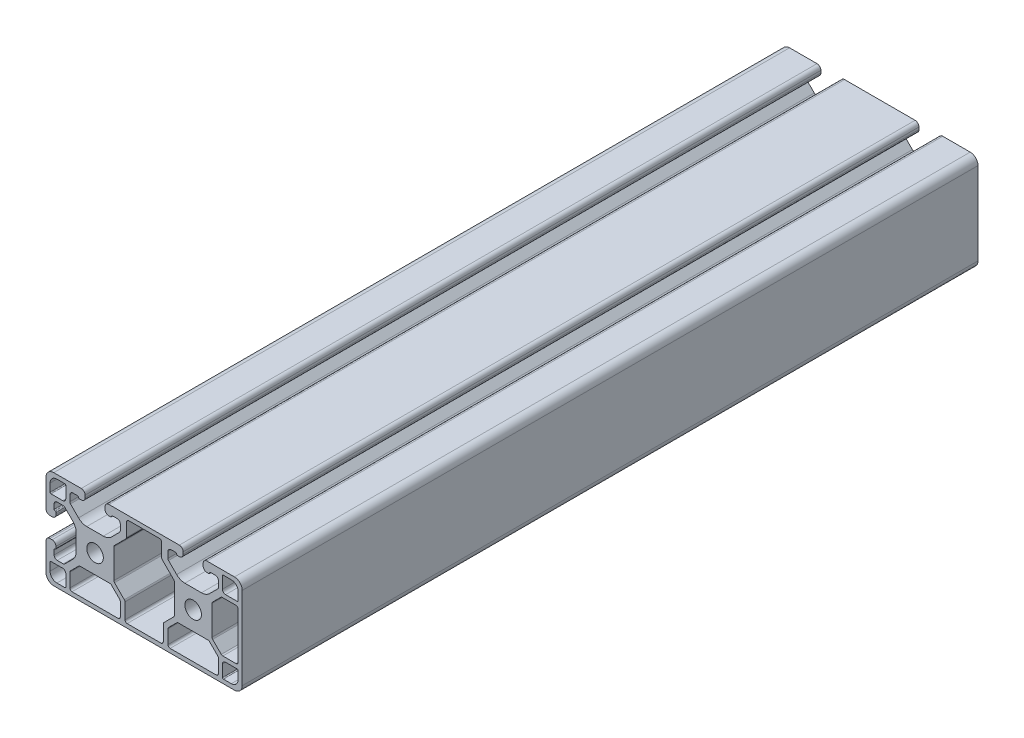
SolidWorks part; units mm, degrees
material "6105-T5 Aluminum"
ref_plane "Front Plane" through (0, 0, 0) normal (0, 0, 1) x (1, 0, 0)
ref_plane "Top Plane" through (0, 0, 0) normal (0, 1, 0) x (1, 0, 0)
ref_plane "Right Plane" through (0, 0, 0) normal (1, 0, 0) x (0, 0, -1)
sketch "Sketch1" plane through (0, 0, 0) normal (0, 0, 1) x (1, 0, 0)
  line L0 (-57.9695, -11.9365) -> (-53.2063, -11.9365)
  line L1 (-51.9365, -13.2063) -> (-51.9365, -17.9693)
  line L2 (-52.3165, -18.3492) -> (-55.5555, -18.3492)
  line L3 (-58.3495, -15.5552) -> (-58.3495, -12.3165)
  line L4 (-53.2063, 11.9365) -> (-57.9695, 11.9365)
  line L5 (-58.3495, 12.3165) -> (-58.3495, 15.5552)
  line L6 (-55.5555, 18.3492) -> (-52.3165, 18.3492)
  line L7 (-51.9365, 17.9693) -> (-51.9365, 13.2063)
  line L8 (13.2063, -11.9365) -> (17.9695, -11.9365)
  line L9 (18.3495, -12.3165) -> (18.3495, -15.5552)
  line L10 (15.5555, -18.3492) -> (12.3165, -18.3492)
  line L11 (11.9365, -17.9693) -> (11.9365, -13.2063)
  line L12 (17.9695, 11.9365) -> (13.2063, 11.9365)
  line L13 (11.9365, 13.2063) -> (11.9365, 17.9693)
  line L14 (12.3165, 18.3492) -> (15.5555, 18.3492)
  line L15 (18.3495, 15.5552) -> (18.3495, 12.3165)
  line L16 (-30.6032, -18.3492) -> (-49.3968, -18.3492)
  line L17 (-50.2857, -17.4603) -> (-50.2857, -11.911)
  line L18 (-50.0254, -11.2824) -> (-46.6858, -7.9429)
  line L19 (-46.0573, -7.6825) -> (-33.9427, -7.6825)
  line L20 (-33.3142, -7.9429) -> (-29.9746, -11.2824)
  line L21 (-29.7143, -11.911) -> (-29.7143, -17.4603)
  line L22 (-28.0699, -10.4935) -> (-32.0571, -6.5062)
  line L23 (-32.3175, -5.8777) -> (-32.3175, 6.0573)
  line L24 (-32.0571, 6.6858) -> (-27.435, 11.308)
  line L25 (-27.1746, 11.9365) -> (-27.1746, 17.4216)
  line L26 (-26.2857, 18.3105) -> (-13.7143, 18.3105)
  line L27 (-12.8254, 17.4216) -> (-12.8254, 11.9365)
  line L28 (-12.565, 11.308) -> (-7.9429, 6.6858)
  line L29 (-7.6825, 6.0573) -> (-7.6825, -5.8777)
  line L30 (-7.9429, -6.5062) -> (-11.9301, -10.4935)
  line L31 (-12.1905, -11.122) -> (-12.1905, -17.4603)
  line L32 (-13.0794, -18.3492) -> (-26.9206, -18.3492)
  line L33 (-27.8095, -17.4603) -> (-27.8095, -11.122)
  line L34 (6.6858, -7.9429) -> (10.0253, -11.2824)
  line L35 (10.2857, -11.911) -> (10.2857, -17.4603)
  line L36 (9.3968, -18.3492) -> (-9.3968, -18.3492)
  line L37 (-10.2857, -17.4603) -> (-10.2857, -11.911)
  line L38 (-10.0254, -11.2824) -> (-6.6858, -7.9429)
  line L39 (-6.0573, -7.6825) -> (6.0572, -7.6825)
  line L40 (11.462, -10.0253) -> (7.9429, -6.5063)
  line L41 (7.6825, -5.8776) -> (7.6825, 6.0573)
  line L42 (7.9429, 6.6858) -> (11.2824, 10.0254)
  line L43 (11.911, 10.2857) -> (17.4216, 10.2857)
  line L44 (18.3105, 9.3968) -> (18.3105, -9.3968)
  line L45 (17.4216, -10.2857) -> (12.0906, -10.2857)
  line L46 (16.8254, 20) -> (5.6381, 20)
  line L47 (4.0635, 18.4254) -> (4.0635, 17.5111)
  line L48 (5.6381, 15.9365) -> (6.3446, 15.9365)
  line L49 (6.7243, 16.3032) -> (6.7253, 16.3317)
  line L50 (7.105, 16.6984) -> (9.0159, 16.6984)
  line L51 (10.2857, 15.4286) -> (10.2857, 12.9885)
  line L52 (10.0254, 12.3599) -> (6.739, 9.0736)
  line L53 (3.3808, 7.6825) -> (-3.3808, 7.6825)
  line L54 (-6.739, 9.0736) -> (-10.0254, 12.3599)
  line L55 (-10.2857, 12.9885) -> (-10.2857, 15.4286)
  line L56 (-9.0159, 16.6984) -> (-7.105, 16.6984)
  line L57 (-6.7253, 16.3317) -> (-6.7243, 16.3032)
  line L58 (-6.3446, 15.9365) -> (-5.6381, 15.9365)
  line L59 (-4.0635, 17.5111) -> (-4.0635, 18.4254)
  line L60 (-5.6381, 20) -> (-34.3619, 20)
  line L61 (-35.9365, 18.4254) -> (-35.9365, 17.5111)
  line L62 (-34.3619, 15.9365) -> (-33.6554, 15.9365)
  line L63 (-33.2757, 16.3032) -> (-33.2747, 16.3317)
  line L64 (-32.895, 16.6984) -> (-30.9841, 16.6984)
  line L65 (-29.7143, 15.4286) -> (-29.7143, 12.9885)
  line L66 (-29.9746, 12.3599) -> (-33.261, 9.0736)
  line L67 (-36.6192, 7.6825) -> (-43.3808, 7.6825)
  line L68 (-46.739, 9.0736) -> (-50.0254, 12.3599)
  line L69 (-50.2857, 12.9885) -> (-50.2857, 15.4286)
  line L70 (-49.0159, 16.6984) -> (-47.105, 16.6984)
  line L71 (-46.7253, 16.3317) -> (-46.7243, 16.3032)
  line L72 (-46.3446, 15.9365) -> (-45.6381, 15.9365)
  line L73 (-44.0635, 17.5111) -> (-44.0635, 18.4254)
  line L74 (-45.6381, 20) -> (-56.8254, 20)
  line L75 (-60, 16.8254) -> (-60, 5.6381)
  line L76 (-58.4254, 4.0635) -> (-57.5111, 4.0635)
  line L77 (-55.9365, 5.6381) -> (-55.9365, 6.3446)
  line L78 (-56.3032, 6.7243) -> (-56.3317, 6.7253)
  line L79 (-56.6984, 7.105) -> (-56.6984, 9.0159)
  line L80 (-55.4286, 10.2857) -> (-52.9885, 10.2857)
  line L81 (-52.3599, 10.0254) -> (-49.0736, 6.739)
  line L82 (-47.6825, 3.3808) -> (-47.6825, -3.3808)
  line L83 (-49.0736, -6.739) -> (-52.3599, -10.0254)
  line L84 (-52.9885, -10.2857) -> (-55.4286, -10.2857)
  line L85 (-56.6984, -9.0159) -> (-56.6984, -7.105)
  line L86 (-56.3317, -6.7253) -> (-56.3032, -6.7243)
  line L87 (-55.9365, -6.3446) -> (-55.9365, -5.6381)
  line L88 (-57.5111, -4.0635) -> (-58.4254, -4.0635)
  line L89 (-60, -5.6381) -> (-60, -16.8254)
  line L90 (-56.8254, -20) -> (16.8254, -20)
  line L91 (20, -16.8254) -> (20, 16.8254)
  arc A0 (-51.9365, -13.2063) -> (-53.2063, -11.9365) centre (-53.2063, -13.2063) ccw
  arc A1 (-52.3165, -18.3492) -> (-51.9365, -17.9693) centre (-52.3165, -17.9693) ccw
  arc A2 (-58.3495, -15.5552) -> (-55.5555, -18.3492) centre (-55.5555, -15.5552) ccw
  arc A3 (-57.9695, -11.9365) -> (-58.3495, -12.3165) centre (-57.9695, -12.3165) ccw
  arc A4 (-58.3495, 12.3165) -> (-57.9695, 11.9365) centre (-57.9695, 12.3165) ccw
  arc A5 (-55.5555, 18.3492) -> (-58.3495, 15.5552) centre (-55.5555, 15.5552) ccw
  arc A6 (-51.9365, 17.9693) -> (-52.3165, 18.3492) centre (-52.3165, 17.9693) ccw
  arc A7 (-53.2063, 11.9365) -> (-51.9365, 13.2063) centre (-53.2063, 13.2063) ccw
  arc A8 (18.3495, -12.3165) -> (17.9695, -11.9365) centre (17.9695, -12.3165) ccw
  arc A9 (15.5555, -18.3492) -> (18.3495, -15.5552) centre (15.5555, -15.5552) ccw
  arc A10 (11.9365, -17.9693) -> (12.3165, -18.3492) centre (12.3165, -17.9693) ccw
  arc A11 (13.2063, -11.9365) -> (11.9365, -13.2063) centre (13.2063, -13.2063) ccw
  arc A12 (11.9365, 13.2063) -> (13.2063, 11.9365) centre (13.2063, 13.2063) ccw
  arc A13 (12.3165, 18.3492) -> (11.9365, 17.9693) centre (12.3165, 17.9693) ccw
  arc A14 (18.3495, 15.5552) -> (15.5555, 18.3492) centre (15.5555, 15.5552) ccw
  arc A15 (17.9695, 11.9365) -> (18.3495, 12.3165) centre (17.9695, 12.3165) ccw
  arc A16 (-30.6032, -18.3492) -> (-29.7143, -17.4603) centre (-30.6032, -17.4603) ccw
  arc A17 (-50.2857, -17.4603) -> (-49.3968, -18.3492) centre (-49.3968, -17.4603) ccw
  arc A18 (-50.0254, -11.2824) -> (-50.2857, -11.911) centre (-49.3968, -11.911) ccw
  arc A19 (-46.0573, -7.6825) -> (-46.6858, -7.9429) centre (-46.0573, -8.5714) ccw
  arc A20 (-33.3142, -7.9429) -> (-33.9427, -7.6825) centre (-33.9427, -8.5714) ccw
  arc A21 (-29.7143, -11.911) -> (-29.9746, -11.2824) centre (-30.6032, -11.911) ccw
  arc A22 (-27.8095, -11.122) -> (-28.0699, -10.4935) centre (-28.6984, -11.122) ccw
  arc A23 (-32.3175, -5.8777) -> (-32.0571, -6.5062) centre (-31.4286, -5.8777) ccw
  arc A24 (-32.0571, 6.6858) -> (-32.3175, 6.0573) centre (-31.4286, 6.0573) ccw
  arc A25 (-27.435, 11.308) -> (-27.1746, 11.9365) centre (-28.0635, 11.9365) ccw
  arc A26 (-26.2857, 18.3105) -> (-27.1746, 17.4216) centre (-26.2857, 17.4216) ccw
  arc A27 (-12.8254, 17.4216) -> (-13.7143, 18.3105) centre (-13.7143, 17.4216) ccw
  arc A28 (-12.8254, 11.9365) -> (-12.565, 11.308) centre (-11.9365, 11.9365) ccw
  arc A29 (-7.6825, 6.0573) -> (-7.9429, 6.6858) centre (-8.5714, 6.0573) ccw
  arc A30 (-7.9429, -6.5062) -> (-7.6825, -5.8777) centre (-8.5714, -5.8777) ccw
  arc A31 (-11.9301, -10.4935) -> (-12.1905, -11.122) centre (-11.3016, -11.122) ccw
  arc A32 (-13.0794, -18.3492) -> (-12.1905, -17.4603) centre (-13.0794, -17.4603) ccw
  arc A33 (-27.8095, -17.4603) -> (-26.9206, -18.3492) centre (-26.9206, -17.4603) ccw
  arc A34 (10.2857, -11.911) -> (10.0253, -11.2824) centre (9.3967, -11.911) ccw
  arc A35 (9.3968, -18.3492) -> (10.2857, -17.4603) centre (9.3968, -17.4603) ccw
  arc A36 (-10.2857, -17.4603) -> (-9.3968, -18.3492) centre (-9.3968, -17.4603) ccw
  arc A37 (-10.0254, -11.2824) -> (-10.2857, -11.911) centre (-9.3968, -11.911) ccw
  arc A38 (-6.0573, -7.6825) -> (-6.6858, -7.9429) centre (-6.0573, -8.5714) ccw
  arc A39 (6.6858, -7.9429) -> (6.0572, -7.6825) centre (6.0572, -8.5715) ccw
  arc A40 (7.6825, -5.8776) -> (7.9429, -6.5063) centre (8.5715, -5.8776) ccw
  arc A41 (7.9429, 6.6858) -> (7.6825, 6.0573) centre (8.5714, 6.0573) ccw
  arc A42 (11.911, 10.2857) -> (11.2824, 10.0254) centre (11.911, 9.3968) ccw
  arc A43 (18.3105, 9.3968) -> (17.4216, 10.2857) centre (17.4216, 9.3968) ccw
  arc A44 (17.4216, -10.2857) -> (18.3105, -9.3968) centre (17.4216, -9.3968) ccw
  arc A45 (11.462, -10.0253) -> (12.0906, -10.2857) centre (12.0906, -9.3967) ccw
  circle A46 centre (0, 0) radius 3.3778
  circle A47 centre (-40, 0) radius 3.3778
  arc A48 (5.6381, 20) -> (4.0635, 18.4254) centre (5.6381, 18.4254) ccw
  arc A49 (4.0635, 17.5111) -> (5.6381, 15.9365) centre (5.6381, 17.5111) ccw
  arc A50 (6.3446, 15.9365) -> (6.7243, 16.3032) centre (6.3446, 16.3165) ccw
  arc A51 (7.105, 16.6984) -> (6.7253, 16.3317) centre (7.105, 16.3185) ccw
  arc A52 (10.2857, 15.4286) -> (9.0159, 16.6984) centre (9.0159, 15.4286) ccw
  arc A53 (10.0254, 12.3599) -> (10.2857, 12.9885) centre (9.3968, 12.9885) ccw
  arc A54 (3.3808, 7.6825) -> (6.739, 9.0736) centre (3.3808, 12.4317) ccw
  arc A55 (-6.739, 9.0736) -> (-3.3808, 7.6825) centre (-3.3808, 12.4317) ccw
  arc A56 (-10.2857, 12.9885) -> (-10.0254, 12.3599) centre (-9.3968, 12.9885) ccw
  arc A57 (-9.0159, 16.6984) -> (-10.2857, 15.4286) centre (-9.0159, 15.4286) ccw
  arc A58 (-6.7253, 16.3317) -> (-7.105, 16.6984) centre (-7.105, 16.3185) ccw
  arc A59 (-6.7243, 16.3032) -> (-6.3446, 15.9365) centre (-6.3446, 16.3165) ccw
  arc A60 (-5.6381, 15.9365) -> (-4.0635, 17.5111) centre (-5.6381, 17.5111) ccw
  arc A61 (-4.0635, 18.4254) -> (-5.6381, 20) centre (-5.6381, 18.4254) ccw
  arc A62 (-34.3619, 20) -> (-35.9365, 18.4254) centre (-34.3619, 18.4254) ccw
  arc A63 (-35.9365, 17.5111) -> (-34.3619, 15.9365) centre (-34.3619, 17.5111) ccw
  arc A64 (-33.6554, 15.9365) -> (-33.2757, 16.3032) centre (-33.6554, 16.3165) ccw
  arc A65 (-32.895, 16.6984) -> (-33.2747, 16.3317) centre (-32.895, 16.3185) ccw
  arc A66 (-29.7143, 15.4286) -> (-30.9841, 16.6984) centre (-30.9841, 15.4286) ccw
  arc A67 (-29.9746, 12.3599) -> (-29.7143, 12.9885) centre (-30.6032, 12.9885) ccw
  arc A68 (-36.6192, 7.6825) -> (-33.261, 9.0736) centre (-36.6192, 12.4317) ccw
  arc A69 (-46.739, 9.0736) -> (-43.3808, 7.6825) centre (-43.3808, 12.4317) ccw
  arc A70 (-50.2857, 12.9885) -> (-50.0254, 12.3599) centre (-49.3968, 12.9885) ccw
  arc A71 (-49.0159, 16.6984) -> (-50.2857, 15.4286) centre (-49.0159, 15.4286) ccw
  arc A72 (-46.7253, 16.3317) -> (-47.105, 16.6984) centre (-47.105, 16.3185) ccw
  arc A73 (-46.7243, 16.3032) -> (-46.3446, 15.9365) centre (-46.3446, 16.3165) ccw
  arc A74 (-45.6381, 15.9365) -> (-44.0635, 17.5111) centre (-45.6381, 17.5111) ccw
  arc A75 (-44.0635, 18.4254) -> (-45.6381, 20) centre (-45.6381, 18.4254) ccw
  arc A76 (-56.8254, 20) -> (-60, 16.8254) centre (-56.8254, 16.8254) ccw
  arc A77 (-60, 5.6381) -> (-58.4254, 4.0635) centre (-58.4254, 5.6381) ccw
  arc A78 (-57.5111, 4.0635) -> (-55.9365, 5.6381) centre (-57.5111, 5.6381) ccw
  arc A79 (-55.9365, 6.3446) -> (-56.3032, 6.7243) centre (-56.3165, 6.3446) ccw
  arc A80 (-56.6984, 7.105) -> (-56.3317, 6.7253) centre (-56.3185, 7.105) ccw
  arc A81 (-55.4286, 10.2857) -> (-56.6984, 9.0159) centre (-55.4286, 9.0159) ccw
  arc A82 (-52.3599, 10.0254) -> (-52.9885, 10.2857) centre (-52.9885, 9.3968) ccw
  arc A83 (-47.6825, 3.3808) -> (-49.0736, 6.739) centre (-52.4317, 3.3808) ccw
  arc A84 (-49.0736, -6.739) -> (-47.6825, -3.3808) centre (-52.4317, -3.3808) ccw
  arc A85 (-52.9885, -10.2857) -> (-52.3599, -10.0254) centre (-52.9885, -9.3968) ccw
  arc A86 (-56.6984, -9.0159) -> (-55.4286, -10.2857) centre (-55.4286, -9.0159) ccw
  arc A87 (-56.3317, -6.7253) -> (-56.6984, -7.105) centre (-56.3185, -7.105) ccw
  arc A88 (-56.3032, -6.7243) -> (-55.9365, -6.3446) centre (-56.3165, -6.3446) ccw
  arc A89 (-55.9365, -5.6381) -> (-57.5111, -4.0635) centre (-57.5111, -5.6381) ccw
  arc A90 (-58.4254, -4.0635) -> (-60, -5.6381) centre (-58.4254, -5.6381) ccw
  arc A91 (-60, -16.8254) -> (-56.8254, -20) centre (-56.8254, -16.8254) ccw
  arc A92 (16.8254, -20) -> (20, -16.8254) centre (16.8254, -16.8254) ccw
  arc A93 (20, 16.8254) -> (16.8254, 20) centre (16.8254, 16.8254) ccw
extrude "Extrude1" add sketch "Sketch1" against normal blind 300
